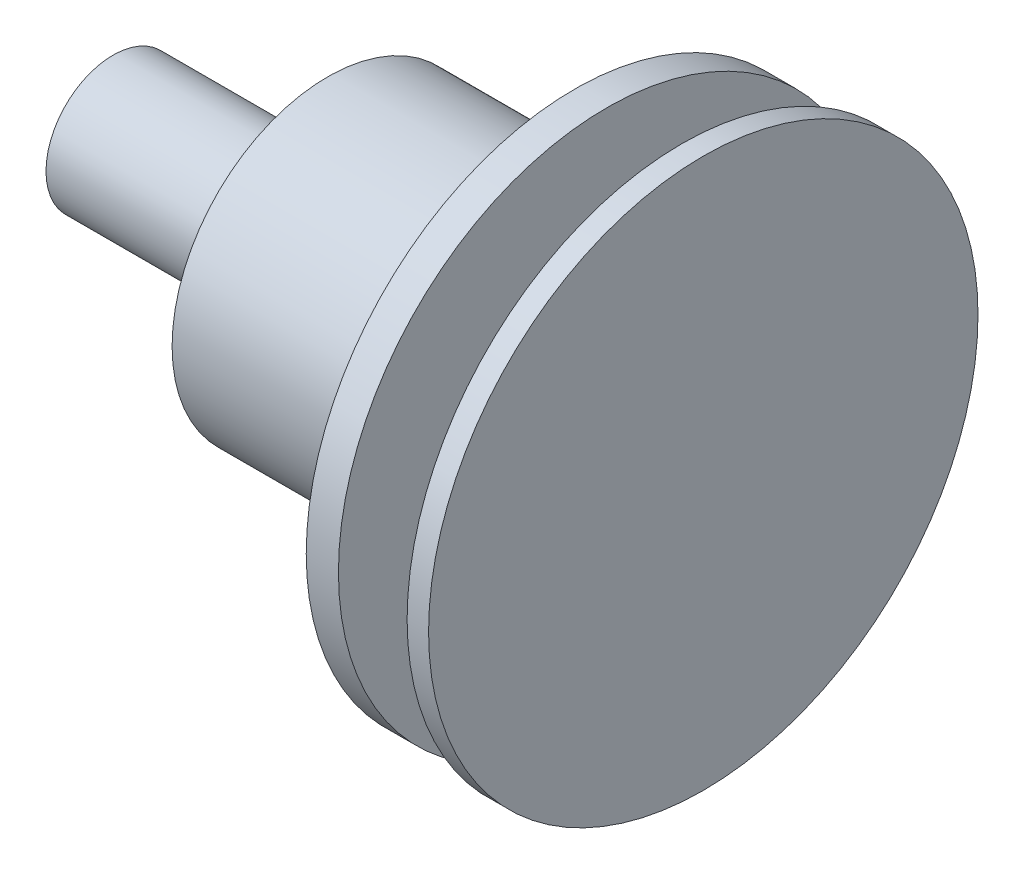
SolidWorks part; units mm, degrees
ref_plane "Front Plane" through (0, 0, 0) normal (0, 0, 1) x (1, 0, 0)
ref_plane "Top Plane" through (0, 0, 0) normal (0, 1, 0) x (1, 0, 0)
ref_plane "Right Plane" through (0, 0, 0) normal (1, 0, 0) x (0, 0, -1)
sketch "Sketch1" plane through (0, 0, 0) normal (0, 0, 1) x (1, 0, 0)
  line L9 (0, 0) -> (0, 7.9375)
  line L12 (67.31, 32.512) -> (69.85, 32.512)
  line L13 (69.85, 32.512) -> (69.85, 0)
  line L18 (0, 0) -> (69.85, 0) construction
  line L19 (69.85, 0) -> (0, 0)
  line L20 (0, 7.9375) -> (25.4, 7.9375)
  line L21 (25.4, 7.9375) -> (25.4, 18.415)
  line L24 (58.42, 31.75) -> (58.42, 19.05)
  line L25 (58.42, 19.05) -> (67.31, 19.05)
  line L26 (67.31, 32.512) -> (67.31, 19.05)
  line L27 (25.4, 18.415) -> (54.61, 18.415)
  line L28 (54.61, 18.415) -> (54.61, 31.75)
  line L29 (54.61, 31.75) -> (58.42, 31.75)
  dimension "D1" = 31.75
  dimension "D2" = 2.54
  dimension "D3" = 18.415
  dimension "D4" = 25.4
  dimension "D5" = 44.45
  dimension "D6" = 15.24
  dimension "D7" = 3.81
  dimension "D8" = 12.7
  dimension "D9" = 13.462
  dimension "D10" = 7.9375
revolve "Revolve7" add sketch "Sketch1" angle 360 about L18
